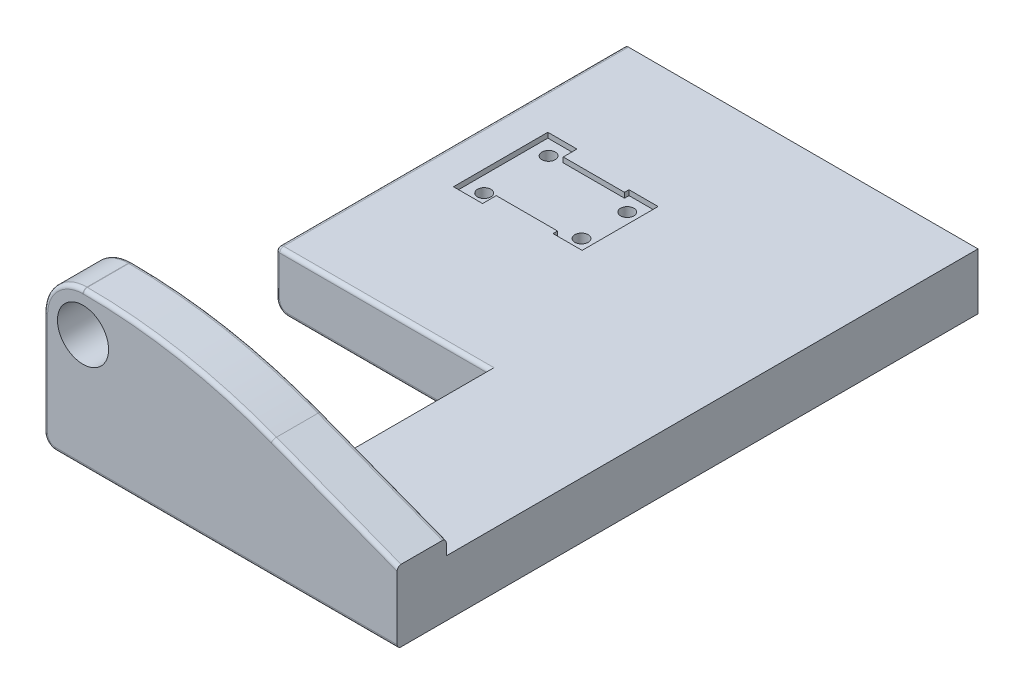
SolidWorks part; units mm, degrees
ref_plane "Front Plane" through (0, 0, 0) normal (0, 0, 1) x (1, 0, 0)
ref_plane "Top Plane" through (0, 0, 0) normal (0, 1, 0) x (1, 0, 0)
ref_plane "Right Plane" through (0, 0, 0) normal (1, 0, 0) x (0, 0, -1)
sketch "Sketch1" plane through (0, 0, 0) normal (0, 1, 0) x (1, 0, 0)
  line L0 (27.7243, -2.5797) -> (27.7243, 43.9203)
  line L2 (-26.7757, 230.9203) -> (-26.7757, 43.9203)
  line L4 (318.2243, 289.9203) -> (318.2243, -15.0797)
  line L5 (27.7243, 43.9203) -> (-26.7757, 43.9203)
  line L6 (-26.7757, 230.9203) -> (27.7243, 230.9203)
  line L7 (27.7243, 230.9203) -> (27.7243, 277.4203)
  line L9 (-26.7757, 289.9203) -> (-26.7757, 277.4203)
  line L10 (-26.7757, 277.4203) -> (27.7243, 277.4203)
  line L12 (-26.7757, -15.0797) -> (-26.7757, -2.5797)
  line L14 (-26.7757, -2.5797) -> (27.7243, -2.5797)
  line L15 (-26.7757, 289.9203) -> (318.2243, 289.9203)
  line L16 (318.2243, -15.0797) -> (-26.7757, -15.0797)
  dimension "D1" = 345
  dimension "D2" = 345
  dimension "D3" = 305
  dimension "D4" = 59
  dimension "D5" = 59
  dimension "D6" = 187
  dimension "D7" = 12.5
  dimension "D8" = 12.5
  dimension "D9" = 54.5
  dimension "D10" = 54.5
  dimension "D11" = 270
  dimension "D12" = 270
  dimension "D13" = 270
  dimension "D14" = 270
  dimension "D15" = 90
  dimension "D16" = 90
  dimension "D17" = 270
  dimension "D18" = 270
  dimension "D19" = 90
  dimension "D20" = 90
  dimension "D21" = 270
  dimension "D22" = 270
  dimension "D23" = 54.5
  dimension "D24" = 46.5
  dimension "D25" = 54.5
  dimension "D26" = 46.5
extrude "Boss-Extrude1" add sketch "Sketch1" along normal blind 14.3
sketch "Sketch2" plane through (0, 14.3, 0) normal (0, 1, 0) x (1, 0, 0)
  line L0 (-13.2757, 91.6103) -> (9.0943, 91.6103) construction
  line L2 (27.7243, 230.9203) -> (-26.7757, 230.9203) construction
  line L3 (-26.7757, 230.9203) -> (-26.7757, 43.9203) construction
  line L4 (-13.2757, 183.2303) -> (9.0943, 183.2303) construction
  line L5 (5.6943, 191.7453) -> (-9.8757, 191.7453)
  line L6 (-9.8757, 174.7153) -> (5.6943, 174.7153)
  line L7 (13.0943, 192.8903) -> (13.0943, 173.5703)
  line L8 (-17.2757, 195.2303) -> (-17.2757, 171.2303)
  line L9 (-17.2757, 195.2303) -> (-9.8757, 195.2303)
  line L10 (-9.8757, 195.2303) -> (-9.8757, 191.7453)
  line L11 (13.0943, 192.8903) -> (5.6943, 192.8903)
  line L12 (5.6943, 192.8903) -> (5.6943, 191.7453)
  line L13 (13.0943, 173.5703) -> (5.6943, 173.5703)
  line L14 (5.6943, 173.5703) -> (5.6943, 174.7153)
  line L15 (-17.2757, 171.2303) -> (-9.8757, 171.2303)
  line L16 (-9.8757, 171.2303) -> (-9.8757, 174.7153)
  line L28 (5.6943, 100.1253) -> (-9.8757, 100.1253)
  line L29 (-9.8757, 83.0953) -> (5.6943, 83.0953)
  line L30 (13.0943, 101.2703) -> (13.0943, 81.9503)
  line L31 (-17.2757, 103.6103) -> (-17.2757, 79.6103)
  line L32 (-17.2757, 103.6103) -> (-9.8757, 103.6103)
  line L33 (-9.8757, 103.6103) -> (-9.8757, 100.1253)
  line L34 (13.0943, 101.2703) -> (5.6943, 101.2703)
  line L35 (5.6943, 101.2703) -> (5.6943, 100.1253)
  line L36 (13.0943, 81.9503) -> (5.6943, 81.9503)
  line L37 (5.6943, 81.9503) -> (5.6943, 83.0953)
  line L38 (-17.2757, 79.6103) -> (-9.8757, 79.6103)
  line L39 (-9.8757, 79.6103) -> (-9.8757, 83.0953)
  line L40 (-26.7757, 43.9203) -> (27.7243, 43.9203) construction
  circle A1 centre (-13.2757, 191.4203) radius 1.5
  circle A2 centre (-13.2757, 175.0403) radius 1.5
  circle A3 centre (9.0943, 189.0503) radius 1.5
  circle A4 centre (9.0943, 177.4103) radius 1.5
  circle A9 centre (-13.2757, 99.8003) radius 1.5
  circle A10 centre (-13.2757, 83.4203) radius 1.5
  circle A11 centre (9.0943, 97.4303) radius 1.5
  circle A12 centre (9.0943, 85.7903) radius 1.5
  point P0 (-13.2757, 191.4203)
  point P5 (-13.2757, 175.0403)
  point P6 (9.0943, 189.0503)
  point P7 (9.0943, 177.4103)
  point P12 (-2.0907, 174.7153)
  point P15 (-2.0907, 183.2303)
  point P16 (-2.0907, 191.7453)
  point P21 (-17.2757, 183.2303)
  point P23 (13.0943, 183.2303)
  point P34 (-13.2757, 99.8003)
  point P36 (-13.2757, 83.4203)
  point P37 (9.0943, 97.4303)
  point P38 (9.0943, 85.7903)
  point P43 (-2.0907, 83.0953)
  point P46 (-2.0907, 91.6103)
  point P47 (-2.0907, 100.1253)
  point P52 (-17.2757, 91.6103)
  point P54 (13.0943, 91.6103)
  dimension "D24" = 3
  dimension "D25" = 3
  dimension "D26" = 3
  dimension "D27" = 3
  dimension "D38" = 15.57
  dimension "D39" = 15.57
  dimension "D40" = 0
  dimension "D41" = 0
  dimension "D48" = 3
  dimension "D49" = 3
  dimension "D50" = 3
  dimension "D51" = 3
  dimension "D1" = 39.5
  dimension "D2" = 13.5
  dimension "D3" = 8.19
  dimension "D4" = 8.19
  dimension "D5" = 22.37
  dimension "D6" = 5.82
  dimension "D7" = 5.82
  dimension "D8" = 22.37
  dimension "D9" = 13.5
  dimension "D10" = 13.5
  dimension "D11" = 22.37
  dimension "D12" = 8.515
  dimension "D13" = 8.515
  dimension "D14" = 15.57
  dimension "D15" = 15.57
  dimension "D16" = 0
  dimension "D17" = 0
  dimension "D18" = 4
  dimension "D19" = 4
  dimension "D20" = 24
  dimension "D21" = 0
  dimension "D22" = 0
  dimension "D23" = 19.32
  dimension "D28" = 4
  dimension "D29" = 8.19
  dimension "D30" = 8.19
  dimension "D31" = 22.37
  dimension "D32" = 5.82
  dimension "D33" = 5.82
  dimension "D34" = 22.37
  dimension "D35" = 22.37
  dimension "D36" = 8.515
  dimension "D37" = 8.515
  dimension "D42" = 4
  dimension "D43" = 4
  dimension "D44" = 24
  dimension "D45" = 0
  dimension "D46" = 0
  dimension "D47" = 19.32
  dimension "D52" = 4
  dimension "D53" = 13.5
  dimension "D54" = 39.5
  dimension "D55" = 4
  dimension "D56" = 4
  dimension "D57" = 3.84
  dimension "D58" = 3.84
  dimension "D59" = 3.84
  dimension "D60" = 3.84
extrude "Cut-Extrude1" cut sketch "Sketch2" against normal blind 1.3
hole_wizard "CSK for M3 Oval Head Machine Screw1" positions "Sketch5" profile "Sketch6" countersink size "M3" standard "ANSI Metric" end condition through all
sketch "Sketch5" plane through (0, 0, 0) normal (0, -1, 0) x (-1, 0, 0)
  point P0 (13.2757, 191.4203)
  point P3 (13.2757, 175.0403)
  point P6 (-9.0943, 177.4103)
  point P9 (-9.0943, 189.0503)
  point P12 (13.2757, 83.4203)
  point P15 (13.2757, 99.8003)
  point P18 (-9.0943, 97.4303)
  point P21 (-9.0943, 85.7903)
sketch "Sketch6" plane through (-13.2757, 0, -191.4203) normal (1, 0, 0) x (0, 0, -1)
  line L0 (0, 0) -> (0, 14.3)
  line L1 (0, 14.3) -> (1.7, 14.3)
  line L2 (1.7, 14.3) -> (1.7, 1.45)
  line L3 (1.7, 1.45) -> (3.15, 0)
  line L5 (3.15, 0) -> (0, 0)
  line L6 (-1.7, 1.45) -> (-3.15, 0) construction
  line L11 (0, -6.35) -> (0, 107.95) construction
  dimension "Thru Hole Dia." = 3.4
  dimension "Thru Hole Depth" = 14.3
  dimension "Near C'Sink Dia." = 6.3
  dimension "Near C'Sink Angle" = 90
sketch "Sketch7" plane through (0, 14.3, 0) normal (0, 1, 0) x (1, 0, 0)
  line L0 (-2.0907, 191.7453) -> (-2.0907, 174.7153) construction
  line L1 (5.6943, 191.7453) -> (-9.8757, 191.7453) construction
  line L2 (-9.8757, 174.7153) -> (5.6943, 174.7153) construction
  line L3 (13.0943, 183.2303) -> (-2.0907, 183.2303) construction
  line L4 (13.0943, 173.5703) -> (13.0943, 192.8903) construction
  line L5 (13.0943, 183.2303) -> (13.0943, 216.7303)
  line L6 (13.0943, 183.2303) -> (13.0943, 149.7303)
  line L7 (13.0943, 149.7303) -> (63.0943, 149.7303)
  line L8 (13.0943, 216.7303) -> (28.0943, 224.2303)
  line L9 (28.0943, 224.2303) -> (43.0943, 224.2303)
  line L10 (43.0943, 224.2303) -> (63.0943, 207.2303)
  line L12 (63.0943, 207.2303) -> (63.0943, 149.7303)
  line L13 (-2.0907, 100.1253) -> (-2.0907, 83.0953) construction
  line L14 (5.6943, 100.1253) -> (-9.8757, 100.1253) construction
  line L15 (13.0943, 91.6103) -> (13.0943, 125.1103)
  line L16 (13.0943, 91.6103) -> (13.0943, 58.1103)
  line L17 (13.0943, 58.1103) -> (63.0943, 58.1103)
  line L18 (13.0943, 125.1103) -> (28.0943, 132.6103)
  line L19 (28.0943, 132.6103) -> (43.0943, 132.6103)
  line L20 (43.0943, 132.6103) -> (63.0943, 115.6103)
  line L21 (63.0943, 115.6103) -> (63.0943, 58.1103)
  line L22 (-9.8757, 83.0953) -> (5.6943, 83.0953) construction
  line L23 (-2.0907, 91.6103) -> (13.0943, 91.6103) construction
  line L24 (13.0943, 81.9503) -> (13.0943, 101.2703) construction
  dimension "D1" = 33.5
  dimension "D2" = 33.5
  dimension "D3" = 50
  dimension "D4" = 15
  dimension "D5" = 7.5
  dimension "D6" = 15
  dimension "D7" = 17
  dimension "D8" = 33.5
  dimension "D9" = 33.5
  dimension "D10" = 50
  dimension "D11" = 15
  dimension "D12" = 7.5
  dimension "D13" = 15
  dimension "D14" = 17
  dimension "D15" = 0
  dimension "D16" = 0
sketch "Sketch8" plane through (0, 0, 15.0797) normal (0, 0, 1) x (1, 0, 0)
  line L0 (-26.7757, 14.3) -> (73.2243, 14.3)
  line L1 (-26.7757, 14.3) -> (318.2243, 14.3) construction
  line L2 (-26.7757, 14.3) -> (-26.7757, 29.3)
  line L3 (73.2243, 14.3) -> (31.4467, 30.3683)
  line L4 (-16.7757, 39.3) -> (-16.6565, 39.3)
  arc A1 (-26.7757, 29.3) -> (-16.7757, 39.3) centre (-16.7757, 29.3) cw
  arc A2 (31.4467, 30.3683) -> (-16.6565, 39.3) centre (-16.6565, -94.7) ccw
  circle A3 centre (-16.7757, 29.3) radius 6.5
  point P9 (-4.1107, 29.3)
  point P12 (8.2243, 39.3)
  dimension "D5" = 10
  dimension "D8" = 134
  dimension "D9" = 13
  dimension "D1" = 100
  dimension "D2" = 15
  dimension "D3" = 25
  dimension "D4" = 65
  dimension "D6" = 22.665
  dimension "D7" = 15
extrude "Boss-Extrude2" add sketch "Sketch8" against normal up to vertex (280 mm away)
sketch "Sketch12" plane through (0, 14.3, 0) normal (0, 1, 0) x (1, 0, 0)
  line L0 (-26.7757, 137.4203) -> (318.2243, 137.4203) construction
  line L1 (-26.7757, 230.9203) -> (-26.7757, 43.9203) construction
  line L2 (318.2243, -15.0797) -> (318.2243, 289.9203) construction
  line L3 (145.7243, 289.9203) -> (145.7243, -15.0797) construction
  line L6 (318.2243, 289.9203) -> (-26.7757, 289.9203) construction
  line L7 (73.2243, -15.0797) -> (318.2243, -15.0797) construction
  line L8 (-26.7757, 289.9203) -> (-26.7757, 277.4203) construction
  line L9 (-13.2757, 191.4203) -> (318.2243, 191.4203) construction
  line L11 (-13.2757, 83.4203) -> (318.2243, 83.4203) construction
  line L12 (318.2243, 232.9203) -> (-26.7757, 232.9203) construction
  line L13 (-26.7757, 41.9203) -> (318.2243, 41.9203) construction
  line L14 (318.2243, 272.9203) -> (-26.7757, 272.9203) construction
  line L15 (318.2243, 1.9203) -> (-26.7757, 1.9203) construction
  point P12 (145.7243, 137.4203)
  point P15 (-26.7757, 283.6703)
  dimension "D1" = 172.5
  dimension "D2" = 172.5
  dimension "D3" = 152.5
  dimension "D4" = 152.5
  dimension "D5" = 41.5
  dimension "D6" = 41.5
  dimension "D7" = 40
  dimension "D8" = 40
ref_plane "Plane1" through (0, 0, -137.4203) normal (0, 0, 1) x (1, 0, 0)
mirror "Mirror1" about plane through (0, 0, -137.4203) normal (0, 0, 1) of bodies 105
sketch "Sketch14" plane through (0, 14.3, 0) normal (0, 1, 0) x (1, 0, 0)
  line L1 (318.2243, -15.0797) -> (278.2243, -15.0797)
  line L2 (318.2243, -15.0797) -> (318.2243, 58.9203)
  line L3 (318.2243, 58.9203) -> (278.2243, 58.9203)
  line L4 (278.2243, -15.0797) -> (278.2243, 58.9203)
  line L5 (-26.7757, 41.9203) -> (318.2243, 41.9203) construction
  dimension "D1" = 17
  dimension "D2" = 40
extrude "Boss-Extrude4" add sketch "Sketch14" along normal blind 25
sketch "Sketch15" plane through (318.2243, 0, 0) normal (1, 0, 0) x (0, 0, -1)
  line L0 (-15.0797, 39.3) -> (-15.0797, 0) construction
  line L1 (91.6103, 14.3) -> (58.1103, 14.3) construction
  line L3 (1.9203, 24.1038) -> (6.4203, 26.7019)
  line L4 (6.4203, 26.7019) -> (6.4203, 31.8981)
  line L5 (6.4203, 31.8981) -> (1.9203, 34.4962)
  line L6 (1.9203, 34.4962) -> (-2.5797, 31.8981)
  line L7 (-2.5797, 31.8981) -> (-2.5797, 26.7019)
  line L8 (-2.5797, 26.7019) -> (1.9203, 24.1038)
  line L9 (41.9203, 24.1038) -> (46.4203, 26.7019)
  line L10 (46.4203, 26.7019) -> (46.4203, 31.8981)
  line L11 (46.4203, 31.8981) -> (41.9203, 34.4962)
  line L12 (41.9203, 34.4962) -> (37.4203, 31.8981)
  line L13 (37.4203, 31.8981) -> (37.4203, 26.7019)
  line L14 (37.4203, 26.7019) -> (41.9203, 24.1038)
  circle A0 centre (1.9203, 29.3) radius 4.5 construction
  circle A1 centre (41.9203, 29.3) radius 4.5 construction
  point P0 (1.9203, 29.3)
  point P1 (41.9203, 29.3)
  point P2 (-189.9912, 162.9721)
  dimension "D5" = 9
  dimension "D6" = 9
  dimension "D1" = 17
  dimension "D2" = 15
  dimension "D3" = 15
  dimension "D4" = 40
extrude "Cut-Extrude3" cut sketch "Sketch15" against normal blind 4
sketch "Sketch18" plane through (318.2243, 0, 0) normal (1, 0, 0) x (0, 0, -1)
  line L0 (1.9203, 34.4962) -> (1.9203, 24.1038) construction
  line L1 (41.9203, 34.4962) -> (41.9203, 24.1038) construction
  point P8 (1.9203, 29.3)
  point P9 (41.9203, 29.3)
hole_wizard "M5 Clearance Hole1" positions "Sketch19" profile "Sketch20" hole size "M5" standard "ANSI Metric" end condition through all
sketch "Sketch19" plane through (314.2243, 0, 0) normal (1, 0, 0) x (0, 0, -1)
  point P4 (1.9203, 29.3)
  point P7 (41.9203, 29.3)
sketch "Sketch20" plane through (314.2243, 29.3, -1.9203) normal (0, 1, 0) x (0, 0, -1)
  line L0 (0, 0) -> (0, 341)
  line L1 (0, 341) -> (2.75, 341)
  line L2 (2.75, 341) -> (2.75, 0)
  line L5 (2.75, 0) -> (0, 0)
  line L11 (0, -6.35) -> (0, 107.95) construction
  dimension "Thru Hole Dia." = 5.5
  dimension "Thru Hole Depth" = 341
fillet "Fillet1" radius 4 1 edges at (278.2243, 39.3, -21.9203)
mirror "Mirror3" about plane through (0, 0, -137.4203) normal (0, 0, 1) of "Fillet1", "Cut-Extrude3", "Boss-Extrude4", "M5 Clearance Hole1"
fillet "Fillet2" radius 7 1 edges at (318.2243, 0, -137.4203)
fillet "Fillet4" radius 3 1 edges at (-26.7757, 0, -137.4203)
fillet "Fillet5" radius 3 1 edges at (-26.7757, 0, 8.8297)
fillet "Fillet6" radius 3 1 edges at (-26.7757, 0, -283.6703)
fillet "Fillet7" radius 1 8 edges at (52.3355, 22.3342, 15.0797) (7.8062, 37.0482, 15.0797) (-23.8468, 36.3711, 15.0797) (318.2243, 23.15, 15.0797) (-26.7757, 16.15, 15.0797) (316.174, 2.0503, 15.0797) (143.7243, 0, 15.0797) (-25.897, 0.8787, 15.0797)
fillet "Fillet8" radius 1 8 edges at (-26.7757, 16.15, -289.9203) (318.2243, 23.15, -289.9203) (-23.8468, 36.3711, -289.9203) (7.8062, 37.0482, -289.9203) (52.3355, 22.3342, -289.9203) (143.7243, 0, -289.9203) (316.174, 2.0503, -289.9203) (-25.897, 0.8787, -289.9203)
fillet "Fillet9" radius 1 11 edges at (27.7243, 0, -20.6703) (1.9743, 0, 2.5797) (-26.7757, 8.65, -43.9203) (-23.8468, 36.3711, 2.5797) (-16.7161, 39.3, 2.5797) (7.8062, 37.0482, 2.5797) (52.3355, 22.3342, 2.5797) (-26.7757, 16.15, 2.5797) (1.9743, 0, -43.9203) (-25.897, 0.8787, -43.9203) (-25.897, 0.8787, 2.5797)
fillet "Fillet10" radius 1 11 edges at (1.9743, 0, -230.9203) (27.7243, 0, -254.1703) (-26.7757, 8.65, -230.9203) (-26.7757, 16.15, -277.4203) (52.3355, 22.3342, -277.4203) (7.8062, 37.0482, -277.4203) (-16.7161, 39.3, -277.4203) (-23.8468, 36.3711, -277.4203) (-25.897, 0.8787, -230.9203) (1.9743, 0, -277.4203) (-25.897, 0.8787, -277.4203)
fillet "Fillet11" radius 1 5 edges at (0.9743, 14.3, -230.9203) (0.9743, 14.3, -43.9203) (-26.4828, 14.3, -44.2132) (-26.7757, 14.3, -137.4203) (-26.4828, 14.3, -230.6274)
sketch "Sketch21" plane through (0, 14.3, 0) normal (0, 1, 0) x (1, 0, 0)
  line L0 (-26.7757, 44.9203) -> (-26.7757, 229.9203) construction
  line L1 (278.2243, 58.9203) -> (278.2243, -15.0797) construction
  line L3 (152.9743, 19.9203) -> (278.2243, 19.9203) construction
  line L4 (222.0993, 14.9203) -> (209.0993, 14.9203)
  line L5 (222.0993, 14.9203) -> (222.0993, 11.4203)
  line L6 (222.0993, 11.4203) -> (209.0993, 11.4203)
  line L7 (209.0993, 14.9203) -> (209.0993, 11.4203)
  line L8 (222.0993, 24.9203) -> (209.0993, 24.9203)
  line L9 (222.0993, 24.9203) -> (222.0993, 28.4203)
  line L10 (222.0993, 28.4203) -> (209.0993, 28.4203)
  line L11 (209.0993, 24.9203) -> (209.0993, 28.4203)
  circle A0 centre (-13.2757, 83.4203) radius 1.7 construction
  point P1 (215.5993, 19.9203)
  dimension "D1" = 63.5
  dimension "D2" = 242.375
  dimension "D3" = 5
  dimension "D4" = 5
  dimension "D5" = 3.5
  dimension "D6" = 3.5
  dimension "D7" = 13
  dimension "D8" = 13
  dimension "D9" = 6.5
  dimension "D10" = 6.5
extrude "Boss-Extrude5" add sketch "Sketch21" along normal blind 33
sketch "Sketch22" plane through (0, 0, -11.4203) normal (0, 0, 1) x (1, 0, 0)
  line L0 (209.0993, 14.3) -> (222.0993, 14.3) construction
  line L1 (222.0993, 47.3) -> (222.0993, 14.3) construction
  line L2 (209.0993, 47.3) -> (209.0993, 14.3) construction
  line L3 (209.0993, 41.3) -> (209.0993, 47.3)
  line L4 (209.0993, 47.3) -> (215.5993, 49.0814)
  line L5 (215.5993, 49.0814) -> (222.0993, 47.3)
  line L6 (222.0993, 47.3) -> (222.0993, 41.3)
  arc A0 (209.0993, 41.3) -> (222.0993, 41.3) centre (215.5993, 40.7792) cw
  point P0 (215.5993, 41.3)
  dimension "D1" = 27
  dimension "D2" = 6.5
extrude "Cut-Extrude4" cut sketch "Sketch22" against normal up to surface (17 mm away) from surface at 0 up to face at (215.5993, 30.8, -28.4203) starting at face at (215.5993, 30.8, -11.4203)
hole_wizard "CSK for M3 Flat Head Machine Screw1" positions "Sketch25" profile "Sketch27" countersink size "M3" standard "ANSI Metric" end condition through all
sketch "Sketch25" plane through (0, 0, -11.4203) normal (0, 0, 1) x (1, 0, 0)
  point P1 (215.5949, 41.2934)
  point P3 (185.0901, 50.4717)
  point P5 (10.6499, 122.6191)
sketch "Sketch27" plane through (215.5949, 41.2934, -11.4203) normal (1, 0, 0) x (0, -1, 0)
  line L0 (0, 0) -> (0, 278.5)
  line L1 (0, 278.5) -> (1.7, 278.5)
  line L2 (1.7, 278.5) -> (1.7, 1.45)
  line L3 (1.7, 1.45) -> (3.15, 0)
  line L5 (3.15, 0) -> (0, 0)
  line L6 (-1.7, 1.45) -> (-3.15, 0) construction
  line L11 (0, -6.35) -> (0, 107.95) construction
  dimension "Thru Hole Dia." = 3.4
  dimension "Thru Hole Depth" = 278.5
  dimension "Near C'Sink Dia." = 6.3
  dimension "Near C'Sink Angle" = 90
mirror "Mirror4" about plane through (0, 0, -137.4203) normal (0, 0, 1) of "Cut-Extrude4", "CSK for M3 Flat Head Machine Screw1", "Boss-Extrude5"
sketch "only_engine_part" plane through (0, 0, 0) normal (0, -1, 0) x (1, 0, 0)
  line L0 (-26.7757, -289.9203) -> (318.2243, -289.9203)
  line L1 (318.2243, -289.9203) -> (318.2243, 15.0797)
  line L2 (318.2243, 15.0797) -> (63.0943, 15.0797)
  line L3 (-23.7757, 15.0797) -> (311.2243, 15.0797) construction
  line L4 (63.0943, 15.0797) -> (63.0943, -132.6103)
  line L5 (63.0943, -132.6103) -> (-26.7757, -132.6103)
  line L6 (-26.7757, -229.9203) -> (-26.7757, -44.9203) construction
  line L7 (-26.7757, -132.6103) -> (-26.7757, -289.9203)
extrude "Cut-Extrude5" cut sketch "only_engine_part" against normal through all
